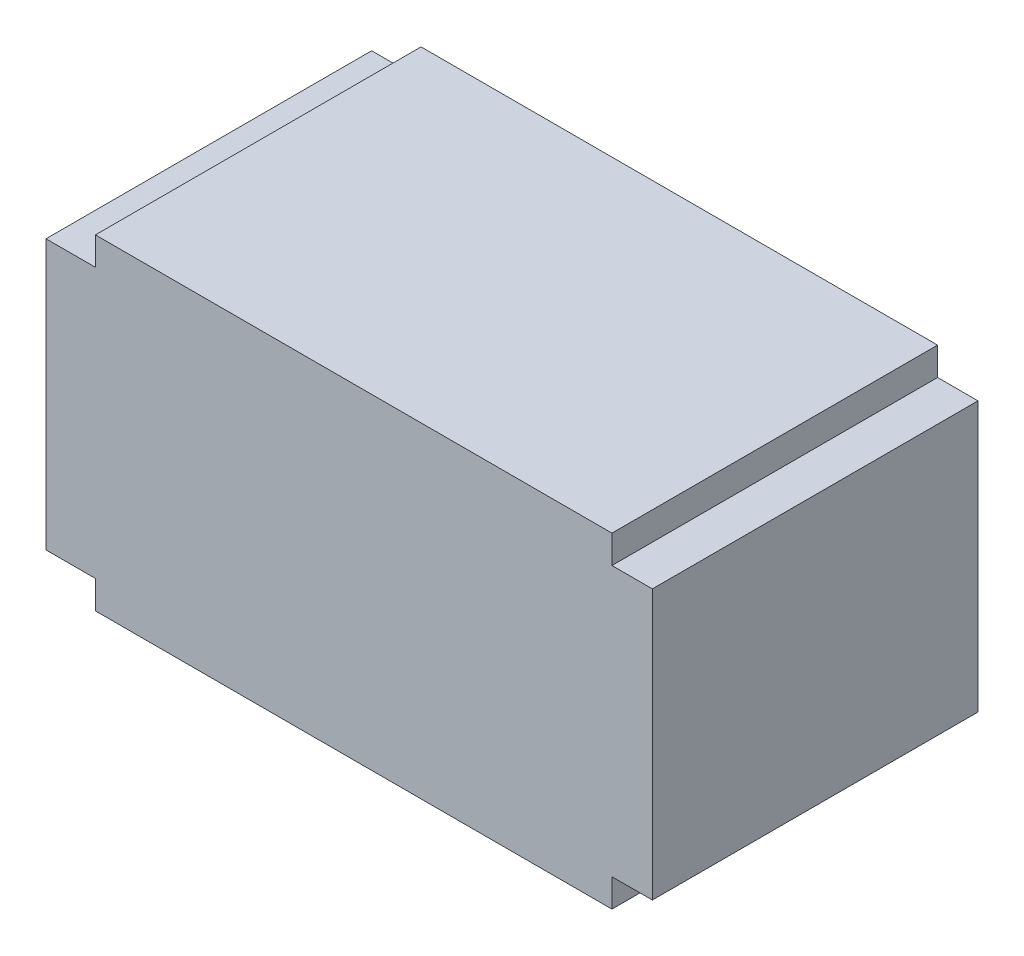
SolidWorks part; units mm, degrees
ref_plane "前视基准面" through (0, 0, 0) normal (0, 0, 1) x (1, 0, 0)
ref_plane "上视基准面" through (0, 0, 0) normal (0, 1, 0) x (1, 0, 0)
ref_plane "右视基准面" through (0, 0, 0) normal (1, 0, 0) x (0, 0, -1)
sketch "草图1" plane through (0, 0, 0) normal (0, 0, 1) x (1, 0, 0)
  line L0 (1.35, -0.6) -> (1.17, -0.6)
  line L1 (1.17, -0.6) -> (1.17, -0.725)
  line L2 (1.17, -0.725) -> (-1.13, -0.725)
  line L3 (-1.13, -0.725) -> (-1.13, -0.6)
  line L4 (-1.13, -0.6) -> (-1.35, -0.6)
  line L5 (-1.35, -0.6) -> (-1.35, 0.6)
  line L6 (-1.35, 0.6) -> (-1.13, 0.6)
  line L7 (-1.13, 0.6) -> (-1.13, 0.725)
  line L8 (-1.13, 0.725) -> (1.17, 0.725)
  line L9 (1.17, 0.725) -> (1.17, 0.6)
  line L10 (1.17, 0.6) -> (1.35, 0.6)
  line L11 (1.35, 0.6) -> (1.35, -0.6)
extrude "Component_Outline" add sketch "草图1" along normal blind 1.45 separate body
sketch3d "3D草图1"
  line L0 (0, 0, 0) -> (1, 0, 0)
  line L1 (0, 0, 0) -> (0, 1, 0)
  line L2 (0, 0, 0) -> (0, 0, 1)
  point P0 (0, 0, 0)
